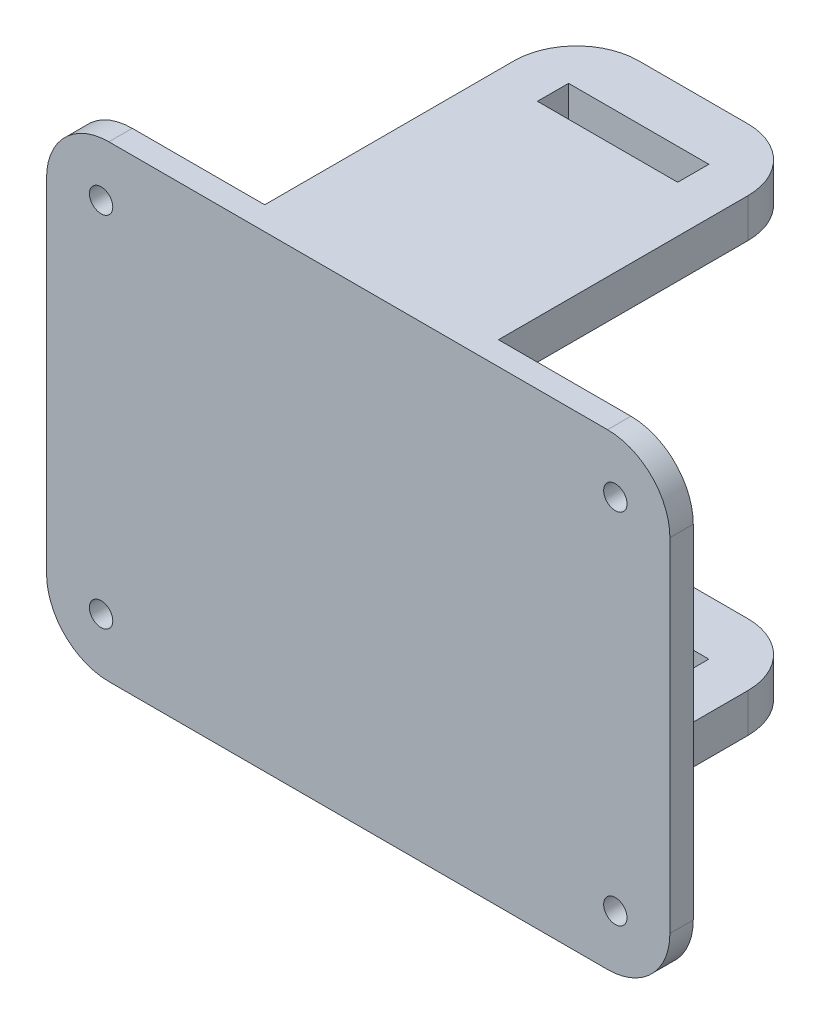
SolidWorks part; units mm, degrees
ref_plane "Front Plane" through (0, 0, 0) normal (0, 0, 1) x (1, 0, 0)
ref_plane "Top Plane" through (0, 0, 0) normal (0, 1, 0) x (1, 0, 0)
ref_plane "Right Plane" through (0, 0, 0) normal (1, 0, 0) x (0, 0, -1)
sketch "Sketch1" plane through (0, 0, 0) normal (0, 0, 1) x (1, 0, 0)
  line L1 (-15, 30) -> (15, 30)
  line L2 (-15, 30) -> (-15, -30)
  line L3 (-15, -30) -> (15, -30)
  line L4 (15, 30) -> (15, -30)
  dimension "D1" = 30
  dimension "D2" = 60
  dimension "D3" = 30
  dimension "D4" = 15
extrude "Boss-Extrude1" add sketch "Sketch1" against normal blind 5
sketch "Sketch2" plane through (0, 0, -5) normal (0, 0, -1) x (-1, 0, 0)
  line L0 (-15, -30) -> (-15, 30) construction
  line L1 (15, -30) -> (-15, -30)
  line L2 (15, -30) -> (15, -25)
  line L3 (15, -25) -> (-15, -25)
  line L4 (-15, -30) -> (-15, -25)
  line L6 (15, 30) -> (-15, 30)
  line L7 (15, 30) -> (15, 25)
  line L8 (15, 25) -> (-15, 25)
  line L9 (-15, 30) -> (-15, 25)
  dimension "D1" = 5
  dimension "D2" = 5
extrude "Boss-Extrude2" add sketch "Sketch2" along normal blind 40
sketch "Sketch3" plane through (0, 0, -5) normal (0, 0, -1) x (-1, 0, 0)
  line L1 (4, -2.5) -> (-4, -2.5)
  line L2 (6, -0.5) -> (6, 0.5)
  line L3 (4, 2.5) -> (-4, 2.5)
  line L4 (-6, -0.5) -> (-6, 0.5)
  arc A0 (4, -2.5) -> (6, -0.5) centre (4, -0.5) ccw
  arc A1 (6, 0.5) -> (4, 2.5) centre (4, 0.5) ccw
  arc A2 (-4, 2.5) -> (-6, 0.5) centre (-4, 0.5) ccw
  arc A3 (-4, -2.5) -> (-6, -0.5) centre (-4, -0.5) cw
  point P7 (6, -2.5)
  point P12 (-6, 2.5)
  point P15 (-6, -2.5)
  dimension "D5" = 2
  dimension "D1" = 12
  dimension "D2" = 5
  dimension "D3" = 2.5
  dimension "D4" = 6
extrude "Boss-Extrude3" add sketch "Sketch3" along normal blind 7
fillet "Fillet1" radius 2 2 edges at (0, -25, -5) (0, 25, -5)
sketch "Sketch4" plane through (15, 0, 0) normal (1, 0, 0) x (0, 0, -1)
  line L0 (45, 30) -> (0, 30) construction
  line L1 (0, -30) -> (5, -30)
  line L2 (0, -30) -> (0, 30)
  line L3 (0, 30) -> (5, 30)
  line L4 (5, -30) -> (5, 30)
extrude "Boss-Extrude4" add sketch "Sketch4" along normal up to surface (25 mm away)
sketch "Sketch5" plane through (-15, 0, 0) normal (-1, 0, 0) x (0, 0, 1)
  line L4 (-5, -30) -> (0, -30)
  line L5 (-5, 30) -> (-5, -30)
  line L6 (0, 30) -> (-5, 30)
  line L7 (0, -30) -> (0, 30)
  line L8 (-5, -30) -> (0, -30)
  line L9 (-5, 30) -> (-5, -30)
  line L10 (0, 30) -> (-5, 30)
  line L11 (0, -30) -> (0, 30)
  dimension "D1" = 0
extrude "Boss-Extrude5" add sketch "Sketch5" along normal up to surface (25 mm away)
fillet "Fillet2" radius 8 4 edges at (-40, 30, -2.5) (-40, -30, -2.5) (40, 30, -2.5) (40, -30, -2.5)
sketch "Sketch6" plane through (0, 0, -5) normal (0, 0, -1) x (-1, 0, 0)
  line L2 (40, 0) -> (-40, 0) construction
  line L3 (40, -22) -> (40, 22) construction
  line L4 (-40, 22) -> (-40, -22) construction
  line L5 (0, -30) -> (0, 30) construction
  line L6 (-15, -30) -> (15, -30) construction
  line L7 (15, 30) -> (-15, 30) construction
  circle A0 centre (33, -23) radius 1.5
  circle A1 centre (-33, -23) radius 1.5
  circle A2 centre (-33, 23) radius 1.5
  circle A3 centre (33, 23) radius 1.5
extrude "Cut-Extrude1" cut sketch "Sketch6" against normal up to surface (5 mm away) up to face at (0, 0, 0)
fillet "Fillet3" radius 8 4 edges at (15, 27.5, -45) (-15, 27.5, -45) (15, -27.5, -45) (-15, -27.5, -45)
sketch "Sketch7" plane through (0, 30, 0) normal (0, 1, 0) x (1, 0, 0)
  line L0 (0, 0) -> (0, 45) construction
  line L1 (-7, 45) -> (7, 45) construction
  line L3 (9, 34) -> (-9, 34)
  line L4 (9, 34) -> (9, 38)
  line L5 (9, 38) -> (-9, 38)
  line L6 (-9, 34) -> (-9, 38)
  dimension "D1" = 18
  dimension "D2" = 7
  dimension "D3" = 9
  dimension "D4" = 4
extrude "Cut-Extrude2" cut sketch "Sketch7" against normal up to surface (60 mm away) up to face at (0, -30, -18.7314)
sketch "Sketch10" plane through (0, 0, 0) normal (0, 0, 1) x (1, 0, 0)
  line L4 (32, 30) -> (-32, 30)
  line L5 (-40, 22) -> (-40, -22)
  line L6 (-32, -30) -> (32, -30)
  line L7 (40, -22) -> (40, 22)
  line L8 (32, 30) -> (-32, 30)
  line L9 (-40, 22) -> (-40, -22)
  line L10 (-32, -30) -> (32, -30)
  line L11 (40, -22) -> (40, 22)
  arc A4 (-32, 30) -> (-40, 22) centre (-32, 22) ccw
  arc A5 (-40, -22) -> (-32, -30) centre (-32, -22) ccw
  arc A6 (32, -30) -> (40, -22) centre (32, -22) ccw
  arc A7 (40, 22) -> (32, 30) centre (32, 22) ccw
  arc A8 (-32, 30) -> (-40, 22) centre (-32, 22) ccw
  arc A9 (-40, -22) -> (-32, -30) centre (-32, -22) ccw
  arc A10 (32, -30) -> (40, -22) centre (32, -22) ccw
  arc A11 (40, 22) -> (32, 30) centre (32, 22) ccw
  dimension "D1" = 0
extrude "Cut-Extrude4" cut sketch "Sketch10" against normal blind 2
